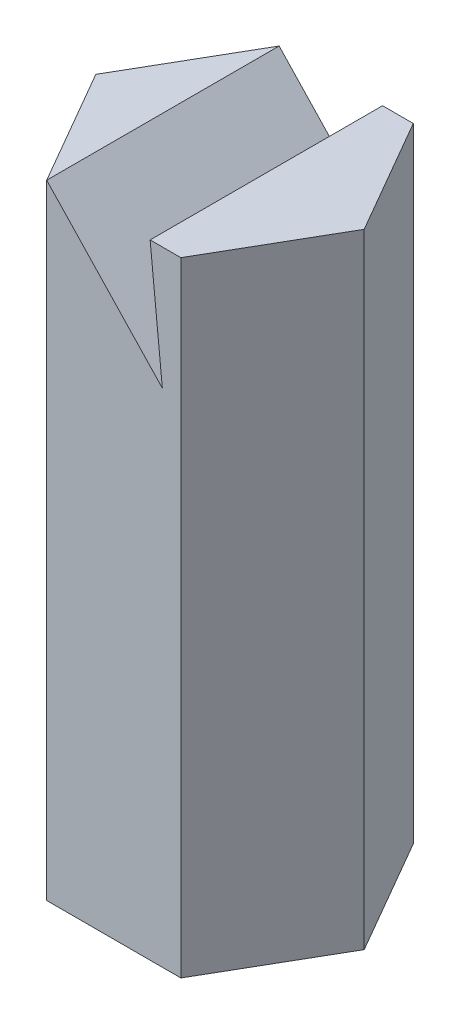
SolidWorks part; units mm, degrees
ref_plane "Front Plane" through (0, 0, 0) normal (0, 0, 1) x (1, 0, 0)
ref_plane "Top Plane" through (0, 0, 0) normal (0, 1, 0) x (1, 0, 0)
ref_plane "Right Plane" through (0, 0, 0) normal (1, 0, 0) x (0, 0, -1)
sketch "Sketch1" plane through (0, 0, 0) normal (0, 1, 0) x (1, 0, 0)
  line L1 (-5.4848, -9.5) -> (5.4848, -9.5)
  line L2 (5.4848, -9.5) -> (10.9697, 0)
  line L3 (10.9697, 0) -> (5.4848, 9.5)
  line L4 (5.4848, 9.5) -> (-5.4848, 9.5)
  line L5 (-5.4848, 9.5) -> (-10.9697, 0)
  line L6 (-10.9697, 0) -> (-5.4848, -9.5)
  circle A0 centre (0, 0) radius 9.5 construction
  point P1 (0, 0)
  point P10 (0, 0)
  point P11 (0, 0)
  dimension "D1" = 19
extrude "Boss-Extrude1" add sketch "Sketch1" along normal blind 51
sketch "Sketch3" plane through (0, 0, 0) normal (0, 0, 1) x (1, 0, 0)
  line L0 (-5.4848, 51) -> (3.9697, 41)
  line L1 (3.9697, 41) -> (2.9697, 51)
  line L2 (2.9697, 51) -> (-5.4848, 51)
  line L3 (10.9697, 51) -> (10.9697, 0) construction
  line L4 (5.4848, 51) -> (10.9697, 51) construction
  point P7 (0, 0)
  dimension "D1" = 7
  dimension "D2" = 8
  dimension "D3" = 10
extrude "Cut-Extrude1" cut sketch "Sketch3" against normal through all both and the other way through all
